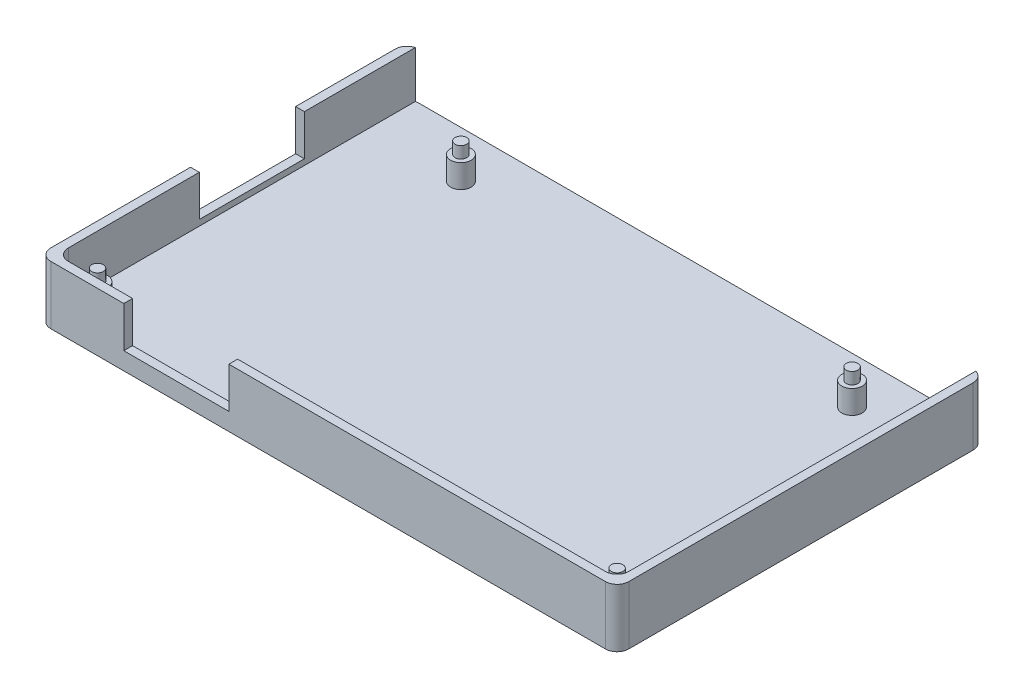
SolidWorks part; units mm, degrees
ref_plane "Front Plane" through (0, 0, 0) normal (0, 0, 1) x (1, 0, 0)
ref_plane "Top Plane" through (0, 0, 0) normal (0, 1, 0) x (1, 0, 0)
ref_plane "Right Plane" through (0, 0, 0) normal (1, 0, 0) x (0, 0, -1)
sketch "Sketch1" plane through (0, 0, 0) normal (0, 1, 0) x (1, 0, 0)
  line L0 (33.5, 25) -> (-33.5, 25) construction
  line L1 (33.5, 25) -> (33.5, -25) construction
  circle A0 centre (-33.5, 25) radius 1
  circle A1 centre (33.5, 25) radius 1
  circle A2 centre (-45.75, -25) radius 1
  circle A3 centre (43.25, -25) radius 1
  point P9 (33.5, 0)
  point P10 (0, 25)
  dimension "D1" = 2
  dimension "D2" = 67
  dimension "D3" = 89
  dimension "D4" = 50
  dimension "D5" = 12.25
extrude "Boss-Extrude1" add sketch "Sketch1" along normal blind 8
sketch "Sketch2" plane through (0, 0, 0) normal (0, 1, 0) x (1, 0, 0)
  circle A0 centre (-33.5, 25) radius 1.75
  circle A1 centre (33.5, 25) radius 1.75
  circle A2 centre (43.25, -25) radius 1.75
  circle A3 centre (-45.75, -25) radius 1.75
  dimension "D1" = 3.5
extrude "Boss-Extrude2" add sketch "Sketch2" along normal blind 6
sketch "Sketch3" plane through (0, 0, 0) normal (0, 1, 0) x (1, 0, 0)
  line L1 (-50.75, 33) -> (48.25, 33)
  line L2 (-50.75, 33) -> (-50.75, -30)
  line L3 (-50.75, -30) -> (48.25, -30)
  line L4 (48.25, 33) -> (48.25, -30)
  circle A0 centre (-45.75, -25) radius 1.75 construction
  circle A1 centre (-45.75, -25) radius 1 construction
  circle A2 centre (43.25, -25) radius 1 construction
  circle A3 centre (33.5, 25) radius 1.75 construction
  dimension "D4" = 8
  dimension "D1" = 5
  dimension "D2" = 5
  dimension "D3" = 5
extrude "Boss-Extrude3" add sketch "Sketch3" along normal blind 2
fillet "Fillet1" radius 2 4 edges at (-50.75, 1, -33) (-50.75, 1, 30) (48.25, 1, 30) (48.25, 1, -33)
sketch "Sketch4" plane through (0, 2, 0) normal (0, 1, 0) x (1, 0, 0)
  line L1 (-47.25, -28.5) -> (44.75, -28.5)
  line L2 (-49.25, -26.5) -> (-49.25, 32.9365)
  line L3 (-50.75, 31) -> (-50.75, -28)
  line L4 (46.75, -26.5) -> (46.75, 32.9365)
  line L5 (-48.75, -30) -> (46.25, -30)
  line L6 (48.25, -28) -> (48.25, 31)
  arc A0 (46.25, -30) -> (48.25, -28) centre (46.25, -28) ccw construction
  arc A1 (44.75, -28.5) -> (46.75, -26.5) centre (44.75, -26.5) ccw
  arc A2 (-49.25, 32.9365) -> (-50.75, 31) centre (-48.75, 31) ccw
  arc A3 (-49.25, -26.5) -> (-47.25, -28.5) centre (-47.25, -26.5) ccw
  arc A4 (46.25, -30) -> (48.25, -28) centre (46.25, -28) ccw
  arc A5 (-50.75, -28) -> (-48.75, -30) centre (-48.75, -28) ccw construction
  circle A6 centre (43.25, -25) radius 1 construction
  arc A7 (48.25, 31) -> (46.75, 32.9365) centre (46.25, 31) ccw
  arc A8 (-48.75, 33) -> (-50.75, 31) centre (-48.75, 31) ccw construction
  arc A9 (-50.75, -28) -> (-48.75, -30) centre (-48.75, -28) ccw
  arc A10 (48.25, 31) -> (46.25, 33) centre (46.25, 31) ccw construction
  circle A11 centre (-45.75, -25) radius 1 construction
  dimension "D1" = 3.5
  dimension "D2" = 3.5
  dimension "D3" = 3.5
extrude "Boss-Extrude4" add sketch "Sketch4" along normal blind 8
sketch "Sketch6" plane through (-50.75, 0, 0) normal (-1, 0, 0) x (0, 0, 1)
  line L0 (-31, 10) -> (28, 10) construction
  line L1 (-13.9365, 10) -> (4.0635, 10)
  line L2 (-13.9365, 10) -> (-13.9365, 3)
  line L3 (-13.9365, 3) -> (4.0635, 3)
  line L4 (4.0635, 10) -> (4.0635, 3)
  line L5 (-32.9365, 10) -> (-32.9365, 2) construction
  dimension "D1" = 19
  dimension "D2" = 18
  dimension "D3" = 7
extrude "Cut-Extrude1" cut sketch "Sketch6" against normal up to next
sketch "Sketch8" plane through (0, 0, 30) normal (0, 0, 1) x (1, 0, 0)
  line L0 (-48.75, 10) -> (46.25, 10) construction
  line L1 (-36.25, 3) -> (-18.25, 3)
  line L2 (-36.25, 3) -> (-36.25, 10)
  line L3 (-36.25, 10) -> (-18.25, 10)
  line L4 (-18.25, 3) -> (-18.25, 10)
  line L5 (-50.75, 0) -> (-50.75, 10) construction
  dimension "D1" = 14.5
  dimension "D2" = 18
  dimension "D3" = 7
extrude "Cut-Extrude2" cut sketch "Sketch8" against normal up to next
